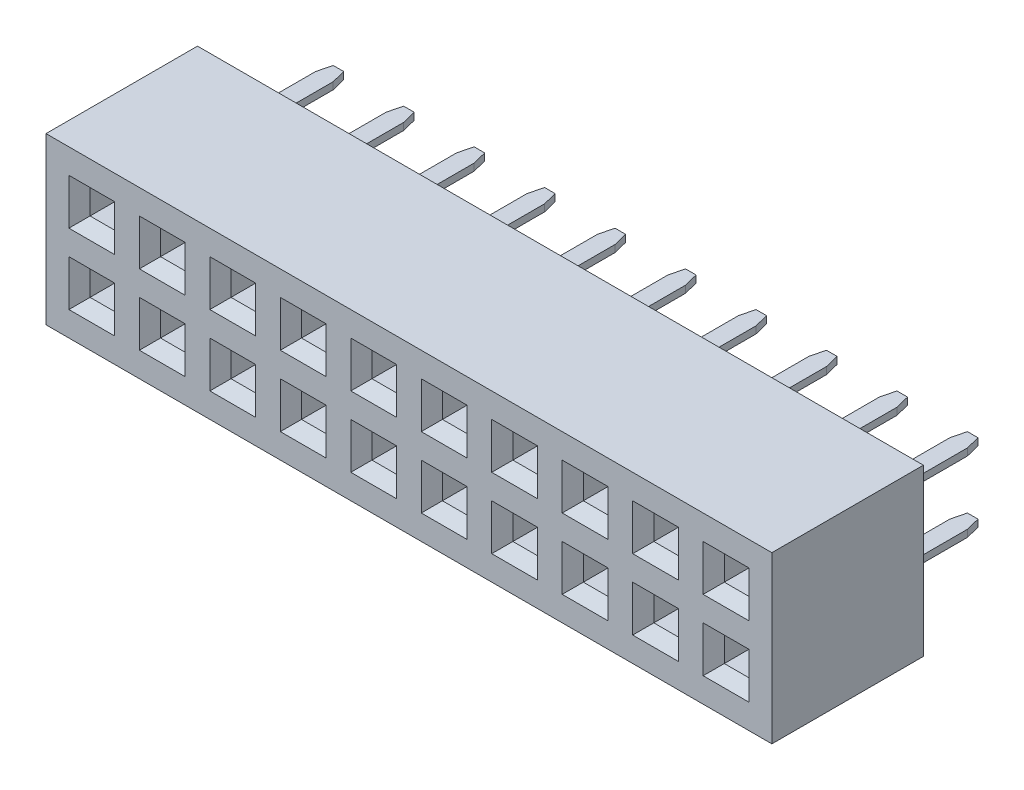
SolidWorks part; units mm, degrees
other "Детальный элемент1"
ref_plane "Спереди" through (0, 0, 0) normal (0, 0, 1) x (1, 0, 0)
ref_plane "Сверху" through (0, 0, 0) normal (0, 1, 0) x (1, 0, 0)
ref_plane "Справа" through (0, 0, 0) normal (1, 0, 0) x (0, 0, -1)
sketch "Эскиз1" plane through (0, 0, 0) normal (0, 0, 1) x (1, 0, 0)
  line L1 (-10.3, 2.35) -> (10.3, 2.35)
  line L2 (-10.3, 2.35) -> (-10.3, -2.35)
  line L3 (-10.3, -2.35) -> (10.3, -2.35)
  line L4 (10.3, 2.35) -> (10.3, -2.35)
  line L5 (-10.3, 2.35) -> (10.3, -2.35) construction
  line L6 (-10.3, -2.35) -> (10.3, 2.35) construction
  point P0 (0, 0)
  dimension "D1" = 4.7
  dimension "D2" = 20.6
extrude "Бобышка-Вытянуть1" add sketch "Эскиз1" along normal blind 4.3
sketch "Эскиз2" plane through (0, 0, 4.3) normal (0, 0, 1) x (1, 0, 0)
  line L0 (-10.3, 2.35) -> (-10.3, -2.35) construction
  line L1 (-9.35, -0.65) -> (-8.65, -0.65)
  line L2 (-9.35, -0.65) -> (-9.35, -1.35)
  line L3 (-9.35, -1.35) -> (-8.65, -1.35)
  line L4 (-8.65, -0.65) -> (-8.65, -1.35)
  line L5 (-9.35, -0.65) -> (-8.65, -1.35) construction
  line L6 (-9.35, -1.35) -> (-8.65, -0.65) construction
  line L7 (-10.3, -2.35) -> (10.3, -2.35) construction
  point P0 (-9, -1)
  dimension "D1" = 1.3
  dimension "D2" = 0.7
  dimension "D3" = 1.35
extrude "Вырез-Вытянуть1" cut sketch "Эскиз2" against normal blind 3
chamfer "Фаска1" distance 0.3 angle 45 4 edges at (-9, -0.65, 4.3) (-9.35, -1, 4.3) (-9, -1.35, 4.3) (-8.65, -1, 4.3)
sketch "Эскиз3" plane through (0, 0, 0) normal (0, 0, -1) x (-1, 0, 0)
  line L0 (10.3, 2.35) -> (10.3, -2.35) construction
  line L1 (8.75, -0.9) -> (9.25, -0.9)
  line L2 (8.75, -0.9) -> (8.75, -1.1)
  line L3 (8.75, -1.1) -> (9.25, -1.1)
  line L4 (9.25, -0.9) -> (9.25, -1.1)
  line L5 (8.75, -0.9) -> (9.25, -1.1) construction
  line L6 (8.75, -1.1) -> (9.25, -0.9) construction
  line L7 (10.3, -2.35) -> (-10.3, -2.35) construction
  point P0 (9, -1)
  point P5 (0, 0)
  dimension "D1" = 1.3
  dimension "D2" = 1.35
  dimension "D3" = 0.2
  dimension "D4" = 0.5
extrude "Бобышка-Вытянуть2" add sketch "Эскиз3" along normal blind 2.7 separate body
chamfer "Фаска2" distance 0.4 distance2 0.1 2 edges at (-8.75, -1, -2.7) (-9.25, -1, -2.7)
pattern_linear "Линейный массив1" count 10 spacing 2 along (1, 0, 0) count 2 spacing 2 along (0, 1, 0) of "Вырез-Вытянуть1", "Фаска1"
pattern_linear "Линейный массив2" count 10 spacing 2 along (1, 0, 0) count 2 spacing 2 along (0, 1, 0) of bodies 109
equation "\"N\"= 10"
equation "\"D2@Эскиз1\"=\"N\"*2+0.6"
equation "\"D1@Линейный массив1\"=\"N\""
